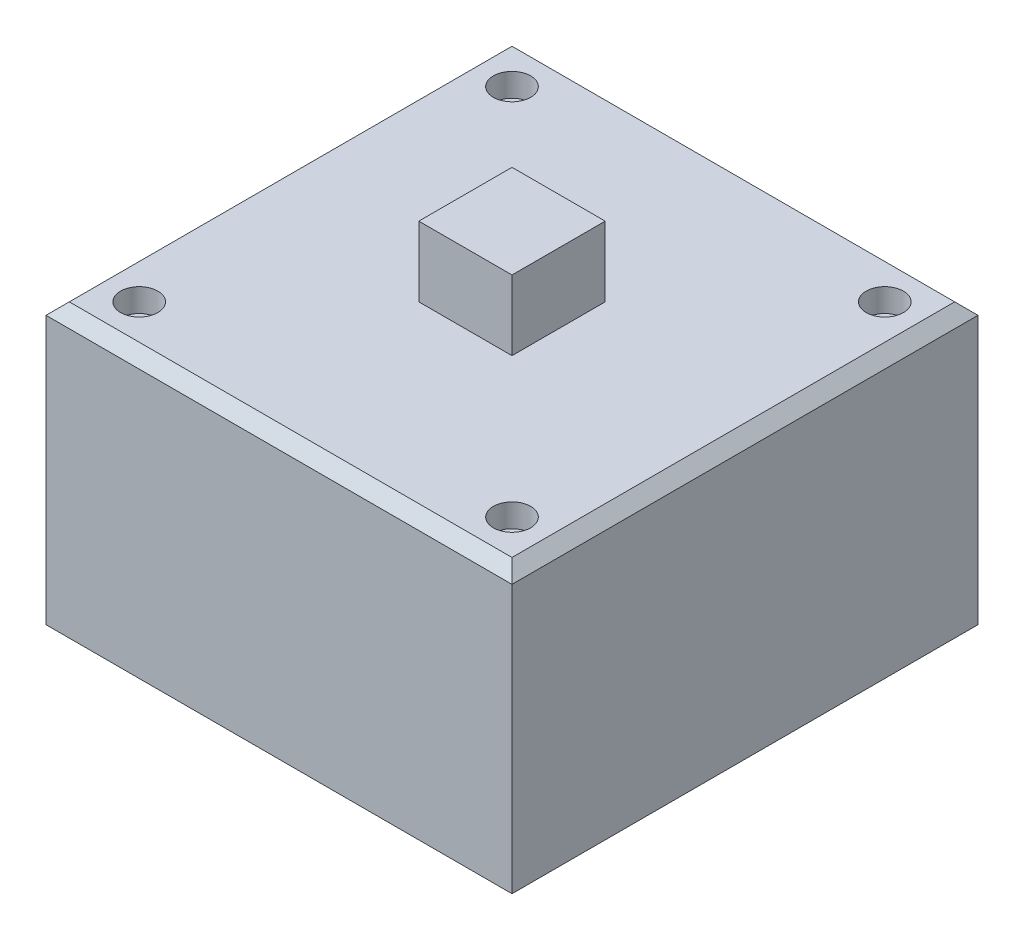
SolidWorks part; units mm, degrees
ref_plane "Front Plane" through (0, 0, 0) normal (0, 0, 1) x (1, 0, 0)
ref_plane "Top Plane" through (0, 0, 0) normal (0, 1, 0) x (1, 0, 0)
ref_plane "Right Plane" through (0, 0, 0) normal (1, 0, 0) x (0, 0, -1)
sketch "Sketch1" plane through (0, 0, 0) normal (0, 1, 0) x (1, 0, 0)
  line L1 (25.4, -25.4) -> (-25.4, -25.4)
  line L2 (25.4, -25.4) -> (25.4, 25.4)
  line L3 (25.4, 25.4) -> (-25.4, 25.4)
  line L4 (-25.4, -25.4) -> (-25.4, 25.4)
  line L5 (25.4, -25.4) -> (-25.4, 25.4) construction
  line L6 (25.4, 25.4) -> (-25.4, -25.4) construction
  point P0 (0, 0)
  dimension "D1" = 50.8
  dimension "D2" = 50.8
extrude "Boss-Extrude1" add sketch "Sketch1" along normal blind 38.1
sketch "Sketch2" plane through (0, 38.1, 0) normal (0, 1, 0) x (1, 0, 0)
  line L0 (-25.4, 25.4) -> (-25.4, -25.4)
  line L5 (5.08, -5.08) -> (-5.08, -5.08)
  line L6 (5.08, -5.08) -> (5.08, 5.08)
  line L11 (5.08, 5.08) -> (-5.08, 5.08)
  line L12 (-5.08, -5.08) -> (-5.08, 5.08)
  line L17 (5.08, -5.08) -> (-5.08, 5.08) construction
  line L18 (5.08, 5.08) -> (-5.08, -5.08) construction
  line L19 (-25.4, -25.4) -> (25.4, -25.4)
  line L20 (25.4, -25.4) -> (25.4, 25.4)
  line L21 (25.4, 25.4) -> (-25.4, 25.4)
  point P0 (0, 0)
  dimension "D1" = 10.16
  dimension "D2" = 10.16
extrude "Cut-Extrude1" cut sketch "Sketch2" against normal blind 7.62 contours L6 L5 L12 L11 | L21 L0 L19 L20
sketch "Sketch3" plane through (0, 30.48, 0) normal (0, 1, 0) x (1, 0, 0)
  line L0 (-25.4, -25.4) -> (-25.4, -20.32) construction
  line L1 (-25.4, 25.4) -> (-25.4, -25.4) construction
  line L2 (-25.4, -20.32) -> (-20.32, -20.32) construction
  line L3 (25.4, -25.4) -> (25.4, -20.32) construction
  line L4 (25.4, -25.4) -> (25.4, 25.4) construction
  line L5 (25.4, -20.32) -> (20.32, -20.32) construction
  circle A0 centre (-20.32, -20.32) radius 2.032
  circle A1 centre (-20.32, 20.32) radius 2.032
  circle A2 centre (20.32, 20.32) radius 2.032
  circle A3 centre (20.32, -20.32) radius 2.032
  circle A4 centre (-20.32, -20.32) radius 1.524
  circle A5 centre (-20.32, 20.32) radius 1.524
  circle A6 centre (20.32, 20.32) radius 1.524
  circle A7 centre (20.32, -20.32) radius 1.524
  point P16 (0, 0)
  point P29 (0, 0)
  dimension "D3" = 4.064
  dimension "D5" = 3.048
  dimension "D1" = 5.08
  dimension "D2" = 5.08
  dimension "D4" = 4
  dimension "D6" = 4
extrude "Cut-Extrude2" cut sketch "Sketch3" against normal blind 2.54
sketch "Sketch4" plane through (0, 30.48, 0) normal (0, 1, 0) x (1, 0, 0)
  circle A0 centre (-20.32, -20.32) radius 1.524
  circle A1 centre (-20.32, 20.32) radius 1.524
  circle A2 centre (20.32, 20.32) radius 1.524
  circle A3 centre (20.32, -20.32) radius 1.524
  point P12 (0, 0)
  dimension "D1" = 3.048
  dimension "D2" = 4
extrude "Cut-Extrude3" cut sketch "Sketch4" against normal blind 20.32
chamfer "Chamfer2" distance 1.27 angle 45 4 edges at (0, 30.48, -25.4) (-25.4, 30.48, 0) (0, 30.48, 25.4) (25.4, 30.48, 0)
